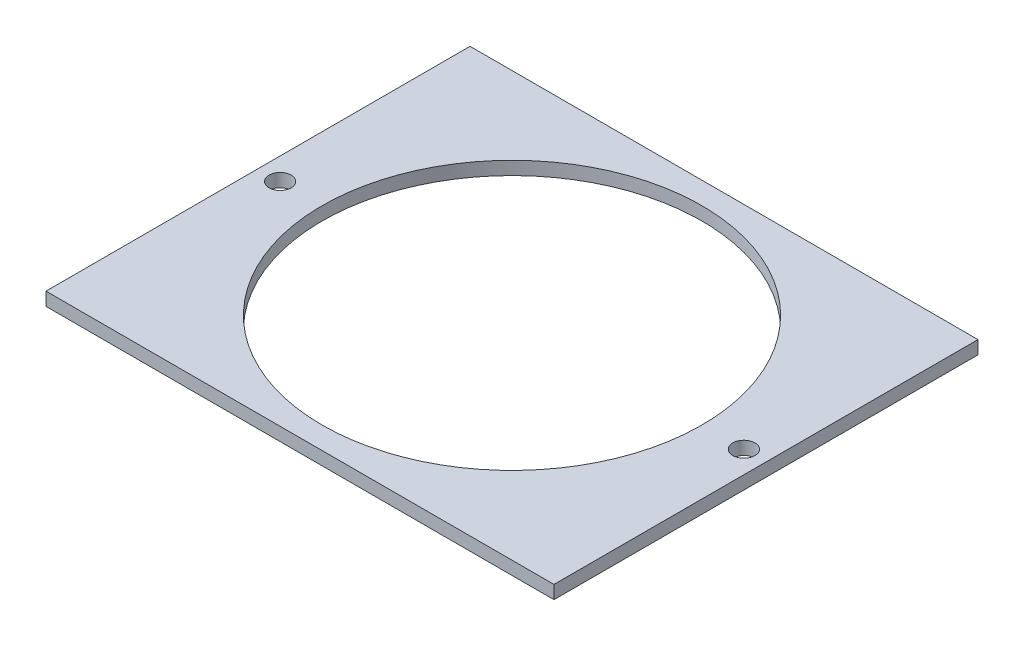
SolidWorks part; units mm, degrees
ref_plane "Front Plane" through (0, 0, 0) normal (0, 0, 1) x (1, 0, 0)
ref_plane "Top Plane" through (0, 0, 0) normal (0, 1, 0) x (1, 0, 0)
ref_plane "Right Plane" through (0, 0, 0) normal (1, 0, 0) x (0, 0, -1)
sketch "Sketch1" plane through (0, 0, 0) normal (0, 1, 0) x (1, 0, 0)
  line L0 (-57.5, 0) -> (-43, 0) construction
  line L1 (-57.5, 48) -> (57.5, 48)
  line L2 (-57.5, 48) -> (-57.5, -48)
  line L3 (-57.5, -48) -> (57.5, -48)
  line L4 (57.5, 48) -> (57.5, -48)
  line L5 (-57.5, 48) -> (57.5, -48) construction
  line L6 (-57.5, -48) -> (57.5, 48) construction
  line L7 (57.5, 0) -> (43, 0) construction
  circle A0 centre (0, 0) radius 43
  circle A1 centre (-52.5, 0) radius 2.5
  circle A2 centre (52.5, 0) radius 2.5
  point P16 (0, 0)
  point P18 (-50.25, 0)
  point P19 (-50.25, 0)
  dimension "D1" = 86
  dimension "D4" = 5
  dimension "D5" = 5
  dimension "D2" = 96
  dimension "D3" = 115
  dimension "D6" = 5
  dimension "D7" = 5
extrude "Boss-Extrude1" add sketch "Sketch1" along normal blind 3
